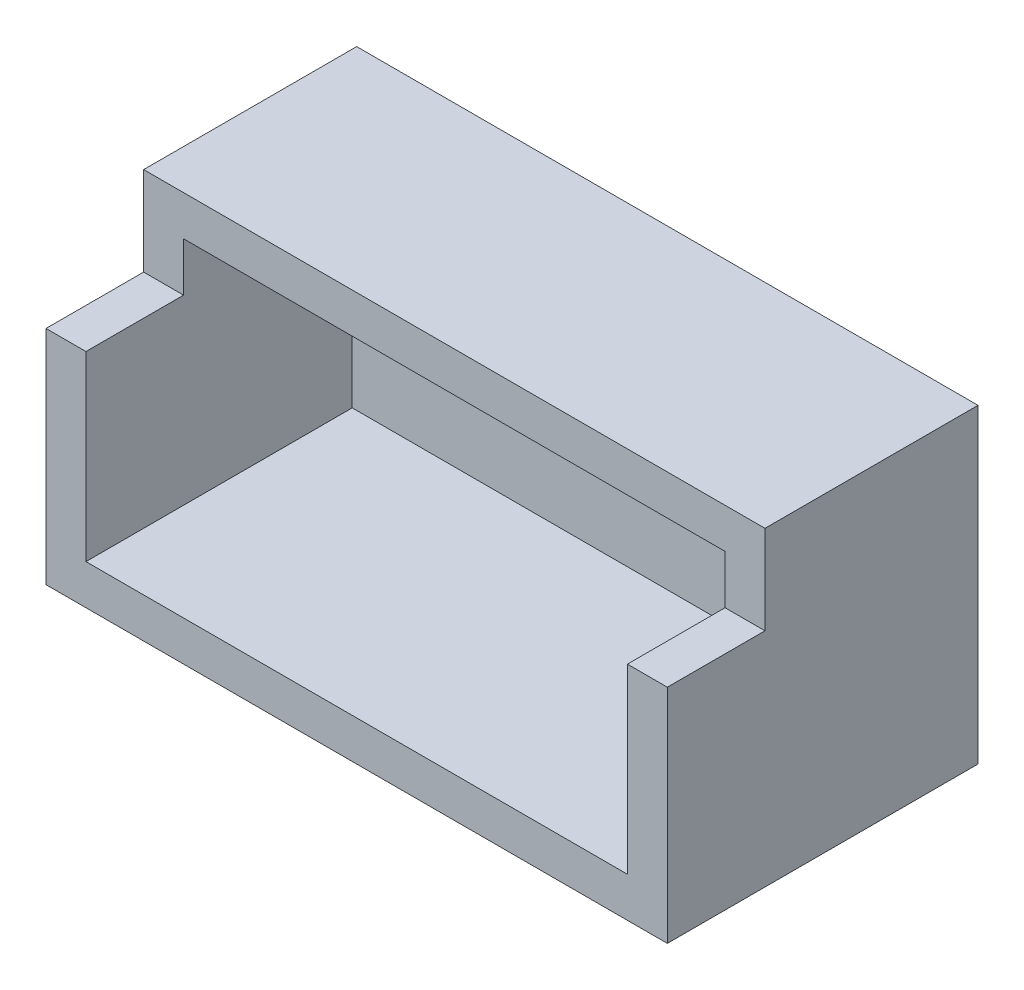
SolidWorks part; units mm, degrees
ref_plane "Front Plane" through (0, 0, 0) normal (0, 0, 1) x (1, 0, 0)
ref_plane "Top Plane" through (0, 0, 0) normal (0, 1, 0) x (1, 0, 0)
ref_plane "Right Plane" through (0, 0, 0) normal (1, 0, 0) x (0, 0, -1)
sketch "Soft_contact_and_wrap_profile" plane through (0, 0, 0) normal (0, 0, 1) x (1, 0, 0)
  line L1 (14, -21) -> (28, -21)
  line L2 (14, -21) -> (14, -14)
  line L3 (14, -14) -> (28, -14)
  line L4 (28, -21) -> (28, -14)
  dimension "D1" = 14
  dimension "D2" = 7
  dimension "D3" = 14
  dimension "D4" = 14
extrude "Soft_contact_and_wrap" add sketch "Soft_contact_and_wrap_profile" along normal blind 7 from offset 1
sketch "Finger_slip_pocket_profile" plane through (0, 0, 0) normal (0, 0, 1) x (1, 0, 0)
  line L1 (14.9, -20.1) -> (27.1, -20.1)
  line L2 (14.9, -20.1) -> (14.9, -14.9)
  line L3 (14.9, -14.9) -> (27.1, -14.9)
  line L4 (27.1, -20.1) -> (27.1, -14.9)
  dimension "D1" = 12.2
  dimension "D2" = 5.2
  dimension "D3" = 14.9
  dimension "D4" = 14.9
extrude "Open_top_slip_pocket" cut sketch "Finger_slip_pocket_profile" along normal blind 7
sketch "Servo_ear_sweep_relief_profile" plane through (0, 0, 0) normal (0, 0, 1) x (1, 0, 0)
  line L1 (13, -16) -> (29, -16)
  line L2 (13, -16) -> (13, -13)
  line L3 (13, -13) -> (29, -13)
  line L4 (29, -16) -> (29, -13)
  dimension "D1" = 16
  dimension "D2" = 3
  dimension "D3" = 13
  dimension "D4" = 13
extrude "Servo_ear_sweep_relief" cut sketch "Servo_ear_sweep_relief_profile" along normal blind 3.2 from offset 3.8
sketch "Pad_capture_M2_profile" plane through (0, 0, 0) normal (0, 0, 1) x (1, 0, 0)
  circle A0 centre (18, -17.5) radius 1.1
  circle A1 centre (24, -17.5) radius 1.1
  dimension "D1" = 2.2
  dimension "D2" = 2.2
  dimension "D3" = 18
  dimension "D4" = 24
  dimension "D5" = 17.5
extrude "Pad_capture_M2" cut sketch "Pad_capture_M2_profile" along normal through all from offset 50
